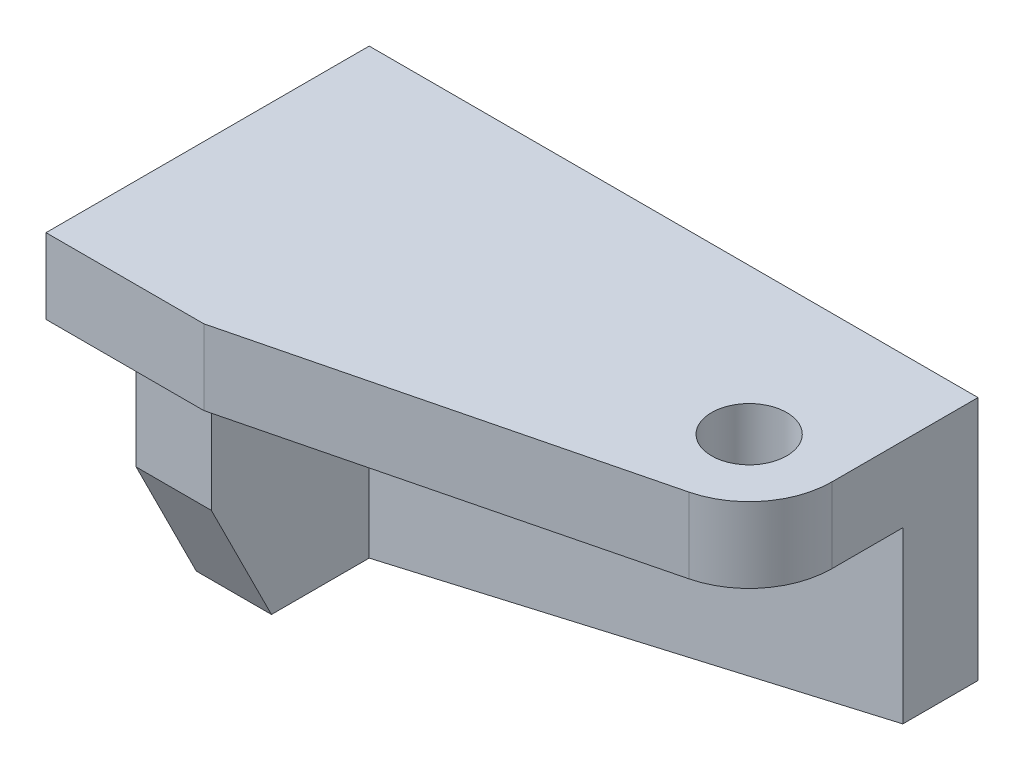
SolidWorks part; units mm, degrees
ref_plane "정면" through (0, 0, 0) normal (0, 0, 1) x (1, 0, 0)
ref_plane "윗면" through (0, 0, 0) normal (0, 1, 0) x (1, 0, 0)
ref_plane "우측면" through (0, 0, 0) normal (1, 0, 0) x (0, 0, -1)
sketch "Sketch1" plane through (0, 0, 0) normal (0, 0, 1) x (1, 0, 0)
  line L0 (0, 0) -> (71, 0)
  line L1 (71, 0) -> (71, -22.6084)
  line L2 (71, -22.6084) -> (0, -39)
  line L3 (0, -39) -> (0, 0)
  dimension "D1" = 77
  dimension "D2" = 39
  dimension "D3" = 71
  dimension "D4" = 0
  dimension "D5" = 0
extrude "Boss-Extrude1" add sketch "Sketch1" along normal blind 10
ref_plane "Plane1" through (0, 0, 0) normal (-1, 0, 0) x (0, 0, 1)
sketch "Sketch3" plane through (0, 0, 0) normal (-1, 0, 0) x (0, 0, 1)
  line L0 (0, 0) -> (31, 0)
  line L1 (31, 0) -> (31, -23)
  line L2 (0, -39) -> (23, -39)
  line L3 (23, -39) -> (31, -23)
  line L4 (0, 0) -> (0, -39)
  dimension "D1" = 31
  dimension "D2" = 23
  dimension "D3" = 23
extrude "Boss-Extrude2" add sketch "Sketch3" along normal blind 10 contours L1 L3 L2 L4 L0
ref_plane "Plane2" through (0, 0, 0) normal (0, 1, 0) x (1, 0, 0)
sketch "Sketch6" plane through (0, 0, 0) normal (0, 1, 0) x (1, 0, 0)
  line L0 (71, 0) -> (71, -19.4462)
  line L4 (71, 0) -> (-10, 0)
  line L6 (-10, 0) -> (-10, -43)
  line L7 (-10, -43) -> (11, -43)
  line L8 (11, -43) -> (62.6611, -30.1194)
  line L9 (71, 0) -> (-10, 0)
  circle A0 centre (60, -19.4462) radius 11
  circle A1 centre (60, -19.4462) radius 5
  dimension "D4" = 22
  dimension "D5" = 10
  dimension "D1" = 43
  dimension "D2" = 166
  dimension "D3" = 21
extrude "Boss-Extrude3" add sketch "Sketch6" along normal blind 10 contours A0 A1 | A0 L0 L4 L6 L7 L8
